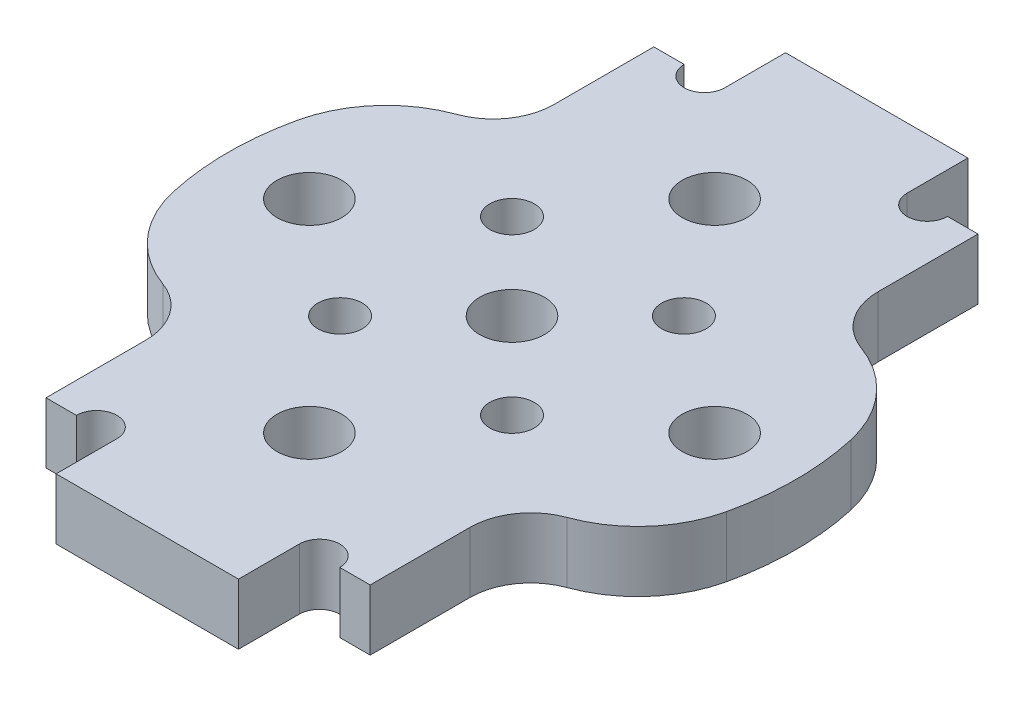
SolidWorks part; units mm, degrees
material "玻纤板"
ref_plane "前视基准面" through (0, 0, 0) normal (0, 0, 1) x (1, 0, 0)
ref_plane "上视基准面" through (0, 0, 0) normal (0, 1, 0) x (1, 0, 0)
ref_plane "右视基准面" through (0, 0, 0) normal (1, 0, 0) x (0, 0, -1)
sketch "草图1" plane through (0, 0, 0) normal (0, 1, 0) x (1, 0, 0)
  line L1 (-8, -15) -> (8, -15)
  line L2 (-8, -15) -> (-8, 15)
  line L3 (-8, 15) -> (8, 15)
  line L4 (8, -15) -> (8, 15)
  line L5 (0, 15) -> (0, -15) construction
  line L6 (-8, 0) -> (8, 0) construction
  circle A0 centre (0, 0) radius 1.6
  circle A1 centre (0, 10) radius 1.6
  circle A2 centre (0, -10) radius 1.6
  point P0 (0, 0)
  dimension "D3" = 3.2
  dimension "D1" = 16
  dimension "D2" = 30
  dimension "D4" = 20
extrude "凸台-拉伸1" add sketch "草图1" along normal blind 3
sketch "草图2" plane through (0, 3, 0) normal (0, 1, 0) x (1, 0, 0)
  line L0 (0, 15) -> (0, -15) construction
  line L1 (8, 15) -> (-8, 15) construction
  line L2 (-8, -15) -> (8, -15) construction
  line L3 (8, 0) -> (0, 0) construction
  line L4 (-4.5, 18) -> (4.5, 18)
  line L5 (-4.5, 18) -> (-4.5, 15)
  line L6 (-4.5, 15) -> (4.5, 15)
  line L7 (4.5, 18) -> (4.5, 15)
  line L8 (0, 15) -> (0, 18) construction
  line L9 (-4.5, 16.5) -> (4.5, 16.5) construction
  line L10 (8, -15) -> (8, 15) construction
  line L11 (-4.5, -15) -> (4.5, -15)
  line L12 (4.5, -18) -> (4.5, -15)
  line L13 (-4.5, -18) -> (4.5, -18)
  line L14 (-4.5, -18) -> (-4.5, -15)
  point P6 (0, 16.5)
  dimension "D1" = 3
  dimension "D2" = 9
extrude "凸台-拉伸2" add sketch "草图2" against normal up to surface (3 mm away) up to face at (0, 0, -8.4)
sketch "草图3" plane through (0, 3, 0) normal (0, 1, 0) x (1, 0, 0)
  line L0 (-4.5, 15) -> (-8, 15) construction
  line L1 (0, 18) -> (0, -18) construction
  line L2 (4.5, 18) -> (-4.5, 18) construction
  line L3 (-4.5, -18) -> (4.5, -18) construction
  line L4 (0, 0) -> (8, 0) construction
  line L5 (8, -15) -> (8, 15) construction
  circle A0 centre (-5.5, 15) radius 1
  circle A1 centre (5.5, 15) radius 1
  circle A2 centre (5.5, -15) radius 1
  circle A3 centre (-5.5, -15) radius 1
  dimension "D1" = 2
extrude "切除-拉伸1" cut sketch "草图3" against normal through all
sketch "草图4" plane through (0, 3, 0) normal (0, 1, 0) x (1, 0, 0)
  line L0 (-8, 15) -> (-8, -15) construction
  line L1 (-10, 0) -> (-14, 0) construction
  line L2 (8, -15) -> (8, 15) construction
  line L3 (8, -7.6) -> (8, 7.6)
  line L4 (-8, 7.6) -> (-8, -7.6)
  line L5 (0, 0) -> (0, -18) construction
  line L6 (-4.5, -18) -> (4.5, -18) construction
  arc A0 (-13.6585, 3.0732) -> (-13.6585, -3.0732) centre (0, 0) ccw
  circle A1 centre (-10, 0) radius 1.6
  circle A2 centre (0, 0) radius 1.6 construction
  arc A3 (13.6585, -3.0732) -> (13.6585, 3.0732) centre (0, 0) ccw
  circle A4 centre (10, 0) radius 1.6
  arc A5 (13.6585, 3.0732) -> (8, 7.6) centre (8, 1.8) ccw
  arc A6 (-13.6585, 3.0732) -> (-8, 7.6) centre (-8, 1.8) cw
  arc A7 (-13.6585, -3.0732) -> (-8, -7.6) centre (-8, -1.8) ccw
  arc A8 (13.6585, -3.0732) -> (8, -7.6) centre (8, -1.8) cw
  dimension "D2" = 4
  dimension "D3" = 11.6
  dimension "D1" = 2
extrude "凸台-拉伸3" add sketch "草图4" against normal up to surface (3 mm away) up to face at (0, 0, 0)
sketch "草图8" plane through (0, 3, 0) normal (0, 1, 0) x (1, 0, 0)
  line L1 (-4.2426, -4.2426) -> (4.2426, -4.2426) construction
  line L2 (-4.2426, -4.2426) -> (-4.2426, 4.2426) construction
  line L3 (-4.2426, 4.2426) -> (4.2426, 4.2426) construction
  line L4 (4.2426, -4.2426) -> (4.2426, 4.2426) construction
  line L5 (0, 4.2426) -> (0, -4.2426) construction
  line L6 (-4.2426, 0) -> (4.2426, 0) construction
  circle A1 centre (-4.2426, 4.2426) radius 1
  circle A2 centre (4.2426, 4.2426) radius 1
  circle A3 centre (4.2426, -4.2426) radius 1
  circle A4 centre (-4.2426, -4.2426) radius 1
  point P0 (0, 0)
  dimension "D1" = 2
  dimension "D2" = 12
extrude "切除-拉伸3" cut sketch "草图8" against normal through all
fillet "圆角1" radius 3 4 edges at (-8, 1.5, 7.6) (8, 1.5, 7.6) (-8, 1.5, -7.6) (8, 1.5, -7.6)
hole_wizard "打孔尺寸(%根据十字)槽沉头木螺钉的类型1" positions "草图9" profile "草图10" countersink size "M2" standard "GB" end condition through all
sketch "草图9" plane through (0, 0, 0) normal (0, 1, 0) x (1, 0, 0)
  point P0 (-4.2426, 4.2426)
  point P4 (4.2426, 4.2426)
  point P8 (-4.2426, -4.2426)
  point P12 (4.2426, -4.2426)
sketch "草图10" plane through (-4.2426, 0, -4.2426) normal (1, 0, 0) x (0, 0, -1)
  line L0 (0, 0) -> (0, 3)
  line L1 (0, 3) -> (1.1, 3)
  line L2 (1.1, 3) -> (1.1, 1.15)
  line L3 (1.1, 1.15) -> (2.25, 0)
  line L5 (2.25, 0) -> (0, 0)
  line L6 (-1.1, 1.15) -> (-2.25, 0) construction
  line L11 (0, -6.35) -> (0, 107.95) construction
  dimension "通孔孔直径" = 2.2
  dimension "通孔孔深度" = 3
  dimension "近端锥形沉头孔直径" = 4.5
  dimension "近端锥形沉头孔角度" = 90
